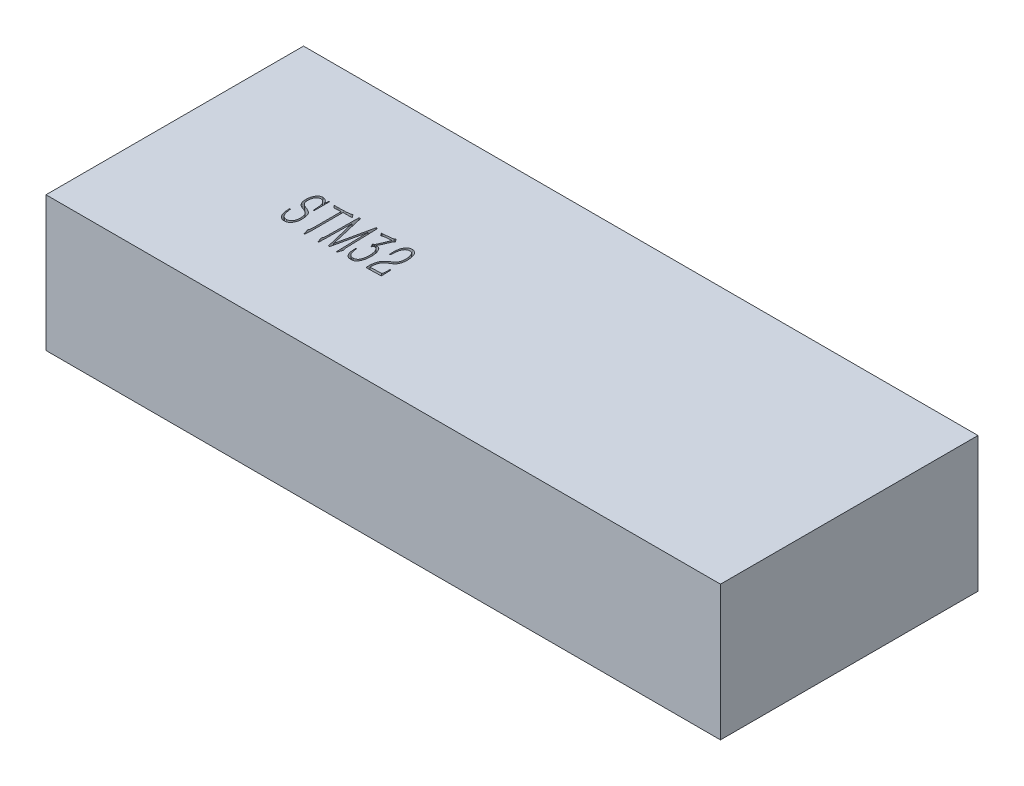
SolidWorks part; units mm, degrees
ref_plane "前视基准面" through (0, 0, 0) normal (0, 0, 1) x (1, 0, 0)
ref_plane "上视基准面" through (0, 0, 0) normal (0, 1, 0) x (1, 0, 0)
ref_plane "右视基准面" through (0, 0, 0) normal (1, 0, 0) x (0, 0, -1)
sketch "草图1" plane through (0, 0, 0) normal (0, 1, 0) x (1, 0, 0)
  line L1 (-27.5, 10.5) -> (27.5, 10.5)
  line L2 (-27.5, 10.5) -> (-27.5, -10.5)
  line L3 (-27.5, -10.5) -> (27.5, -10.5)
  line L4 (27.5, 10.5) -> (27.5, -10.5)
  line L5 (-27.5, 10.5) -> (27.5, -10.5) construction
  line L6 (-27.5, -10.5) -> (27.5, 10.5) construction
  point P0 (0, 0)
extrude "凸台-拉伸1" add sketch "草图1" along normal blind 11
sketch "草图2" plane through (0, 11, 0) normal (0, 1, 0) x (1, 0, 0)
  text T0 "STM32"
extrude "切除-拉伸1" cut sketch "草图2" against normal blind 2
